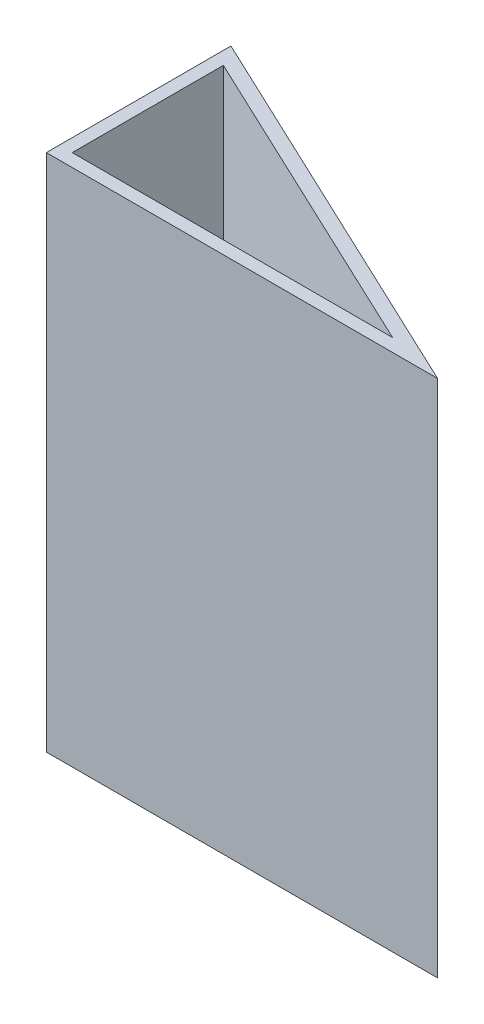
SolidWorks part; units mm, degrees
ref_plane "Front Plane" through (0, 0, 0) normal (0, 0, 1) x (1, 0, 0)
ref_plane "Top Plane" through (0, 0, 0) normal (0, 1, 0) x (1, 0, 0)
ref_plane "Right Plane" through (0, 0, 0) normal (1, 0, 0) x (0, 0, -1)
sketch "Sketch1" plane through (0, 0, 0) normal (0, 1, 0) x (1, 0, 0)
  line L0 (-17.4602, 2.4747) -> (-17.4602, -38.1657)
  line L3 (-17.4602, -38.1657) -> (68.6846, -38.1657)
  line L4 (-17.4602, 2.4747) -> (68.6846, -38.1657)
  point P2 (-17.4602, -39.0753)
  dimension "D1" = 95.25
  dimension "D2" = 86.1448
  dimension "D3" = 40.6403
extrude "Boss-Extrude1" add sketch "Sketch1" along normal blind 114.3
sketch "Sketch2" plane through (0, 114.3, 0) normal (0, 1, 0) x (1, 0, 0)
  line L0 (-14.6065, -2.0469) -> (-14.6065, -35.3209)
  line L1 (-14.6065, -35.3209) -> (55.9253, -35.3209)
  line L2 (-17.4602, 2.4747) -> (68.6846, -38.1657) construction
  line L3 (-14.6065, -2.0469) -> (55.9253, -35.3209)
  line L6 (-17.4602, 2.4747) -> (-17.4602, -38.1657) construction
  line L7 (-17.4602, -38.1657) -> (68.6846, -38.1657) construction
  point P3 (0, 0)
  dimension "D1" = 33.274
  dimension "D2" = 64.744
  dimension "D3" = 25.256
  dimension "D4" = 2.8537
  dimension "D5" = 2.8448
  dimension "D6" = 2.8717
extrude "Cut-Extrude1" cut sketch "Sketch2" against normal blind 114.3
